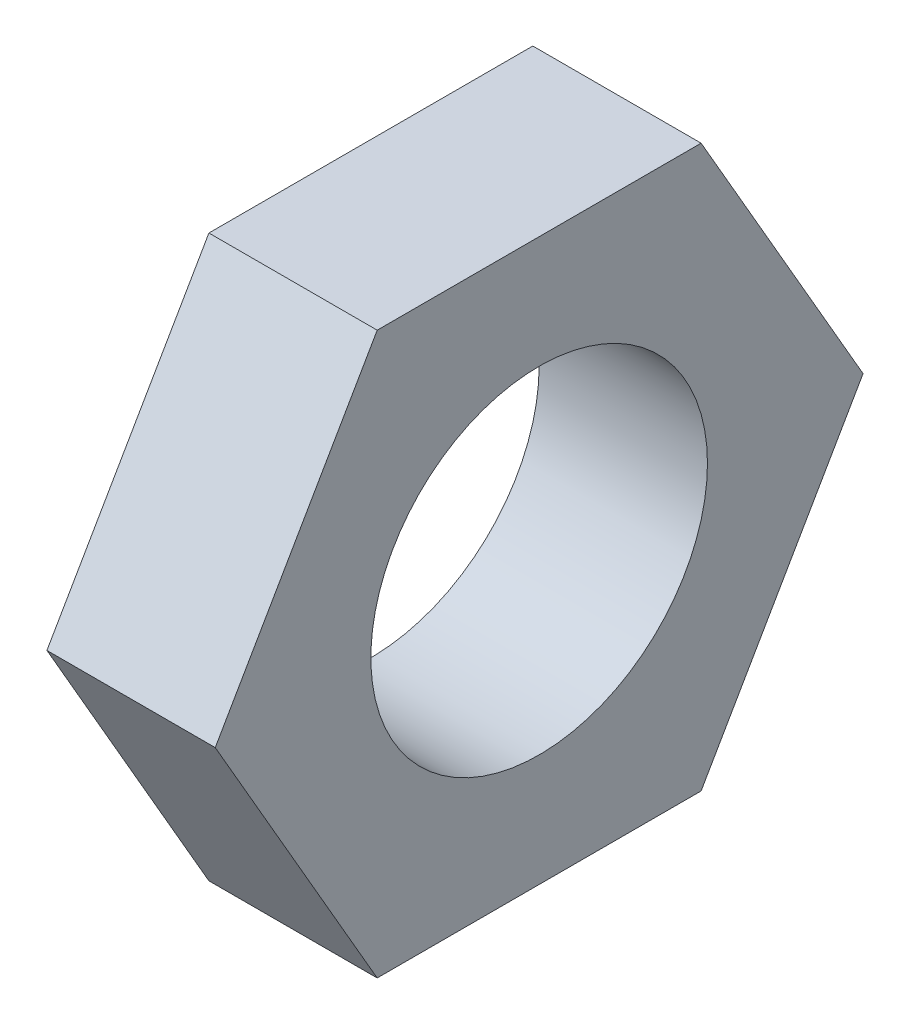
SolidWorks part; units mm, degrees
other "Preload Thin Locknut M6"
ref_plane "Front Plane" through (0, 0, 0) normal (0, 0, 1) x (1, 0, 0)
ref_plane "Top Plane" through (0, 0, 0) normal (0, 1, 0) x (1, 0, 0)
ref_plane "Right Plane" through (0, 0, 0) normal (1, 0, 0) x (0, 0, -1)
sketch3d "Hex nut blank sketch datum points"
  point P0 (20.5, -29, -19.5)
  point P1 (20.5, -19, -19.5)
  point P2 (20.5, -29, -9.5)
ref_plane "Hex nut blank sketch plane" through (20.5, 0, 0) normal (1, 0, 0) x (0, 0, -1)
sketch "Hex nut blank sketch" plane through (20.5, 0, 0) normal (1, 0, 0) x (0, 0, -1)
  line L0 (16.6132, -24) -> (13.7265, -29)
  line L1 (13.7265, -29) -> (16.6132, -34)
  line L2 (16.6132, -34) -> (22.3868, -34)
  line L3 (22.3868, -34) -> (25.2735, -29)
  line L4 (25.2735, -29) -> (22.3868, -24)
  line L5 (22.3868, -24) -> (16.6132, -24)
  circle A0 centre (19.5, -29) radius 5.7735 construction
extrude "Hex nut blank" add sketch "Hex nut blank sketch" along normal blind 3 separate body
sketch3d "M6 thread envelope sketch datum points"
  point P0 (20.4, -29, -19.5)
  point P1 (20.4, -19, -19.5)
  point P2 (20.4, -29, -9.5)
ref_plane "M6 thread envelope sketch plane" through (20.4, 0, 0) normal (1, 0, 0) x (0, 0, -1)
sketch "M6 thread envelope sketch" plane through (20.4, 0, 0) normal (1, 0, 0) x (0, 0, -1)
  circle A0 centre (19.5, -29) radius 3
extrude "M6 thread envelope" cut sketch "M6 thread envelope sketch" along normal blind 3.2
